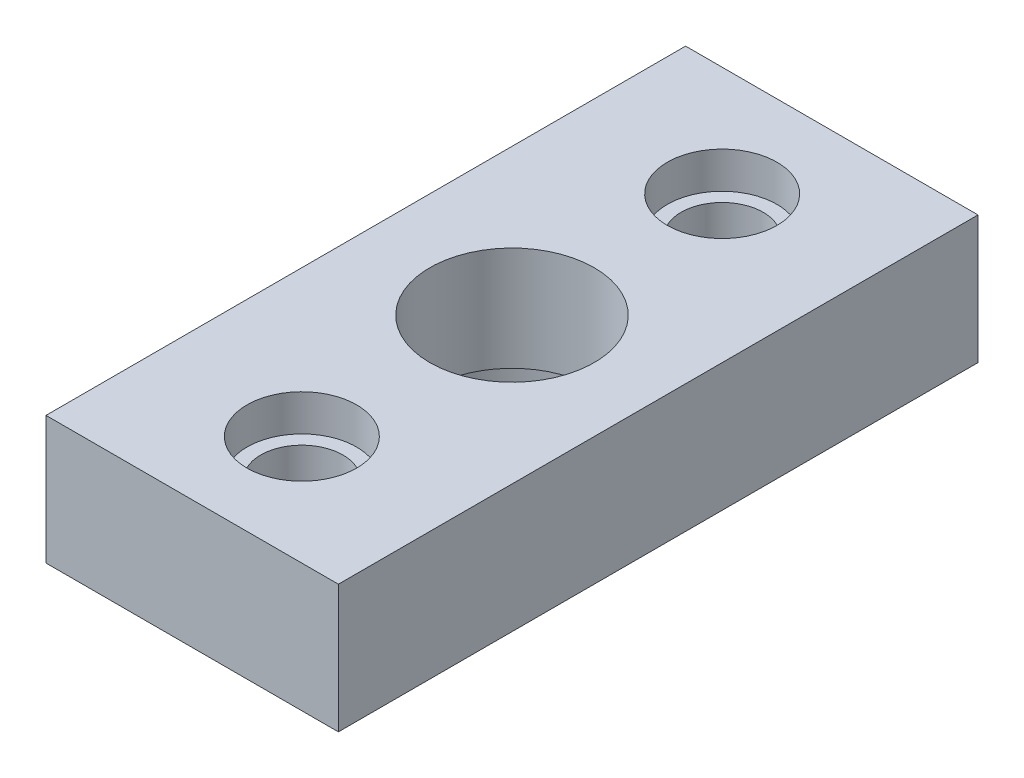
SolidWorks part; units mm, degrees
ref_plane "Front" through (0, 0, 0) normal (0, 0, 1) x (1, 0, 0)
ref_plane "Top" through (0, 0, 0) normal (0, 1, 0) x (1, 0, 0)
ref_plane "Right" through (0, 0, 0) normal (1, 0, 0) x (0, 0, -1)
sketch "草图1" plane through (0, 0, 0) normal (0, 1, 0) x (1, 0, 0)
  line L1 (-8, -17.5) -> (8, -17.5)
  line L2 (-8, -17.5) -> (-8, 17.5)
  line L3 (-8, 17.5) -> (8, 17.5)
  line L4 (8, -17.5) -> (8, 17.5)
  line L5 (-8, -17.5) -> (8, 17.5) construction
  line L6 (-8, 17.5) -> (8, -17.5) construction
  point P0 (0, 0)
  dimension "D1" = 16
  dimension "D2" = 35
extrude "凸台-拉伸1" add sketch "草图1" along normal blind 7
sketch "草图2" plane through (0, 0, 0) normal (0, -1, 0) x (1, 0, 0)
  circle A0 centre (0, 0) radius 5.35
  dimension "D1" = 10.7
extrude "切除-拉伸1" cut sketch "草图2" against normal blind 1.3
sketch "草图3" plane through (0, 1.3, 0) normal (0, -1, 0) x (1, 0, 0)
  circle A0 centre (0, 0) radius 4.5
  dimension "D1" = 9
extrude "切除-拉伸2" cut sketch "草图3" against normal through all
sketch "草图4" plane through (0, 7, 0) normal (0, 1, 0) x (1, 0, 0)
  line L0 (8, -17.5) -> (8, 17.5) construction
  line L1 (8, 17.5) -> (-8, 17.5) construction
  line L2 (-8, -17.5) -> (8, -17.5) construction
  circle A0 centre (0, 11.5) radius 3
  circle A1 centre (0, -11.5) radius 3
  point P0 (0, 11.5)
  point P1 (0, -11.5)
  dimension "D5" = 6
  dimension "D6" = 6
  dimension "D1" = 8
  dimension "D2" = 8
  dimension "D3" = 6
  dimension "D4" = 6
extrude "切除-拉伸3" cut sketch "草图4" against normal blind 2
sketch "草图6" plane through (0, 5, 0) normal (0, 1, 0) x (1, 0, 0)
  circle A0 centre (0, -11.5) radius 2.25
  circle A1 centre (0, 11.5) radius 2.25
  dimension "D1" = 4.5
  dimension "D2" = 4.5
extrude "切除-拉伸4" cut sketch "草图6" against normal through all
